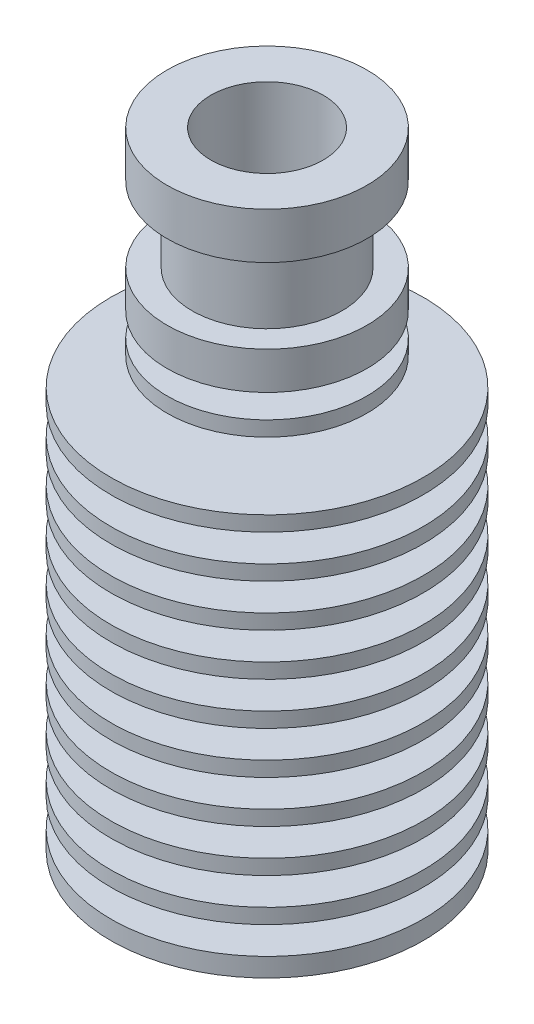
SolidWorks part; units mm, degrees
ref_plane "Přední rovina" through (0, 0, 0) normal (0, 0, 1) x (1, 0, 0)
ref_plane "Horní rovina" through (0, 0, 0) normal (0, 1, 0) x (1, 0, 0)
ref_plane "Pravá rovina" through (0, 0, 0) normal (1, 0, 0) x (0, 0, -1)
sketch "Skica1" plane through (0, 0, 0) normal (0, 0, 1) x (1, 0, 0)
  line L0 (0, 64.6375) -> (0, 60.9375) construction
  line L1 (0, 60.9375) -> (0, 54.9375) construction
  line L2 (0, 54.9375) -> (0, 51.9375) construction
  line L3 (0, 64.6375) -> (8, 64.6375) construction
  line L4 (0, 60.9375) -> (6, 60.9375) construction
  line L5 (0, 54.9375) -> (6, 54.9375) construction
  line L6 (0, 51.9375) -> (8, 51.9375) construction
  line L7 (8, 64.6375) -> (4.5, 64.6375)
  line L8 (8, 64.6375) -> (8, 60.9375)
  line L9 (8, 60.9375) -> (6, 60.9375)
  line L10 (6, 60.9375) -> (6, 54.9375)
  line L11 (8, 54.9375) -> (6, 54.9375)
  line L12 (8, 54.9375) -> (8, 51.9375)
  line L13 (0, 51.9375) -> (4.5, 51.9375) construction
  line L14 (8, 51.9375) -> (4.5, 51.9375)
  line L15 (0, 64.6375) -> (0, 50.0375) construction
  line L16 (0, 64.6375) -> (0, 46.6375) construction
  line L17 (0, 64.6375) -> (0, 14.5375) construction
  line L18 (0, 50.0375) -> (0, 36.4375) construction
  line L19 (0, 36.4375) -> (0, 33.0375) construction
  line L20 (0, 50.0375) -> (8, 50.0375) construction
  line L21 (4, 50.0375) -> (4, 48.8375) construction
  line L22 (4.5, 51.9375) -> (4.5, 50.0375)
  line L23 (4.5, 50.0375) -> (8, 50.0375)
  line L24 (8, 50.0375) -> (8, 48.8375)
  line L25 (8, 48.8375) -> (4, 48.8375)
  line L26 (4, 48.8375) -> (4, 46.6375)
  line L27 (0, 46.6375) -> (12.5, 46.6375) construction
  line L28 (4, 46.6375) -> (12.5, 46.6375)
  line L29 (12.5, 46.6375) -> (12.5, 45.4375)
  line L30 (12.5, 45.4375) -> (4, 45.4375)
  line L31 (4, 45.4375) -> (4, 43.2375)
  line L32 (4, 43.2375) -> (12.5, 43.2375)
  line L33 (12.5, 43.2375) -> (12.5, 42.0375)
  line L34 (12.5, 42.0375) -> (4, 42.0375)
  line L35 (4, 42.0375) -> (4, 39.8375)
  line L36 (4, 39.8375) -> (12.5, 39.8375)
  line L37 (12.5, 39.8375) -> (12.5, 38.6375)
  line L38 (12.5, 38.6375) -> (4, 38.6375)
  line L39 (4, 38.6375) -> (4, 36.4375)
  line L40 (4, 36.4375) -> (12.5, 36.4375)
  line L41 (12.5, 36.4375) -> (12.5, 35.2375)
  line L42 (0, 35.2375) -> (6.5, 35.2375) construction
  line L43 (12.5, 35.2375) -> (6.5, 35.2375)
  line L44 (6.5, 35.2375) -> (6.5, 33.0375)
  line L45 (6.5, 33.0375) -> (12.5, 33.0375)
  line L46 (12.5, 33.0375) -> (12.5, 31.8375)
  line L47 (0, 31.8375) -> (7.5, 31.8375) construction
  line L48 (12.5, 31.8375) -> (7.5, 31.8375)
  line L49 (7.5, 31.8375) -> (7.5, 29.6375)
  line L50 (7.5, 29.6375) -> (12.5, 29.6375)
  line L51 (12.5, 29.6375) -> (12.5, 28.4375)
  line L52 (12.5, 28.4375) -> (7.5, 28.4375)
  line L53 (7.5, 28.4375) -> (7.5, 26.2375)
  line L54 (7.5, 26.2375) -> (12.5, 26.2375)
  line L55 (12.5, 26.2375) -> (12.5, 25.0375)
  line L56 (12.5, 25.0375) -> (7.5, 25.0375)
  line L57 (7.5, 25.0375) -> (7.5, 22.8375)
  line L58 (7.5, 22.8375) -> (12.5, 22.8375)
  line L59 (12.5, 22.8375) -> (12.5, 21.6375)
  line L60 (12.5, 21.6375) -> (7.5, 21.6375)
  line L61 (7.5, 21.6375) -> (7.5, 19.4375)
  line L62 (7.5, 19.4375) -> (12.5, 19.4375)
  line L63 (12.5, 19.4375) -> (12.5, 18.2375)
  line L64 (12.5, 18.2375) -> (7.5, 18.2375)
  line L65 (7.5, 18.2375) -> (7.5, 16.0375)
  line L66 (7.5, 16.0375) -> (12.5, 16.0375)
  line L67 (12.5, 16.0375) -> (12.5, 14.5375)
  line L68 (3, 14.5375) -> (12.5, 14.5375)
  line L69 (0, 14.5375) -> (3, 14.5375) construction
  line L70 (3, 14.5375) -> (3, 31.8375)
  line L71 (0, 36.4375) -> (1, 36.4375) construction
  line L72 (1, 33.0375) -> (1, 31.8375)
  line L73 (1, 33.0375) -> (1, 46.6375)
  line L74 (0, 46.6375) -> (0, 50.6375) construction
  line L75 (0, 50.6375) -> (2, 50.6375) construction
  line L76 (2, 50.6375) -> (2, 46.9362)
  line L77 (2, 46.9362) -> (1, 46.6375)
  line L78 (2, 50.6375) -> (4.5, 52.9746)
  line L79 (4.5, 52.9746) -> (4.5, 64.6375)
  line L80 (1, 31.8375) -> (3, 31.8375)
  dimension "D1" = 3.7
  dimension "D2" = 6
  dimension "D3" = 3
  dimension "D4" = 12.7
  dimension "D5" = 8
  dimension "D6" = 6
  dimension "D7" = 4.5
  dimension "D8" = 14.6
  dimension "D9" = 18
  dimension "D10" = 50.1
  dimension "D11" = 13.6
  dimension "D12" = 3.4
  dimension "D13" = 18.5
  dimension "D14" = 8
  dimension "D15" = 1.2
  dimension "D16" = 2.2
  dimension "D17" = 12.5
  dimension "D18" = 6.5
  dimension "D19" = 7.5
  dimension "D20" = 5
  dimension "D21" = 1
  dimension "D22" = 3
  dimension "D23" = 17.3
  dimension "D25" = 4
  dimension "D26" = 2
  dimension "D27" = 1.0437
  dimension "D28" = 11.6629
  dimension "D29" = 3.4223
revolve "Rotovat1" add sketch "Skica1" angle 360 about L17
